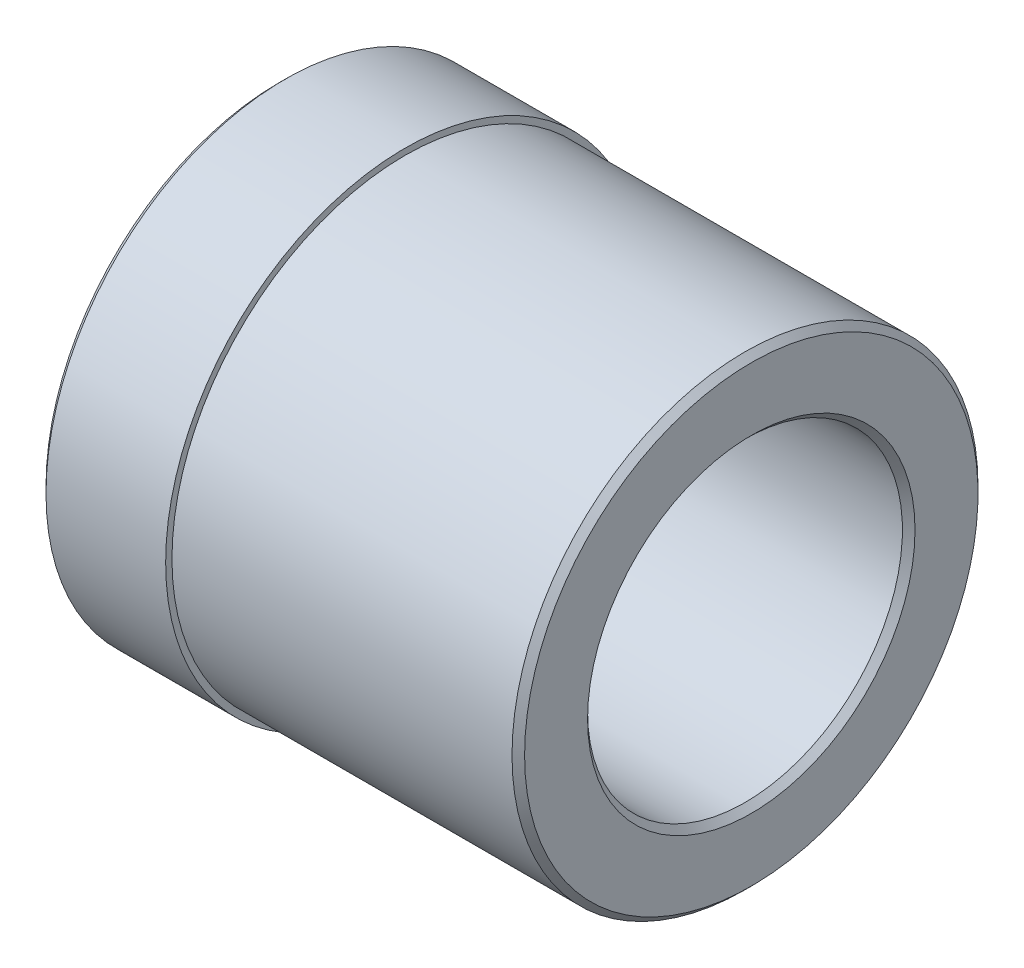
SolidWorks part; units mm, degrees
material "20"
ref_plane "前视基准面" through (0, 0, 0) normal (0, 0, 1) x (1, 0, 0)
ref_plane "上视基准面" through (0, 0, 0) normal (0, 1, 0) x (1, 0, 0)
ref_plane "右视基准面" through (0, 0, 0) normal (1, 0, 0) x (0, 0, -1)
sketch "草图1" plane through (0, 0, 0) normal (0, 0, 1) x (1, 0, 0)
  line L0 (0, 0) -> (105.5195, 0) construction
  line L1 (0, 0) -> (0, 25) construction
  line L2 (0, 25) -> (0, 38)
  line L3 (0, 38) -> (20, 38)
  line L4 (20, 38) -> (20, 37)
  line L5 (20, 37) -> (75, 37)
  line L6 (75, 37) -> (75, 25)
  line L7 (75, 25) -> (0, 25)
  dimension "D1" = 75
  dimension "D2" = 50
  dimension "D3" = 76
  dimension "D4" = 20
  dimension "D5" = 74
revolve "旋转1" add sketch "草图1" angle 360 about L0
chamfer "倒角1" distance 1 angle 45 4 edges at (0, 0, 25) (0, 0, 38) (75, 0, 25) (75, 0, 37)
